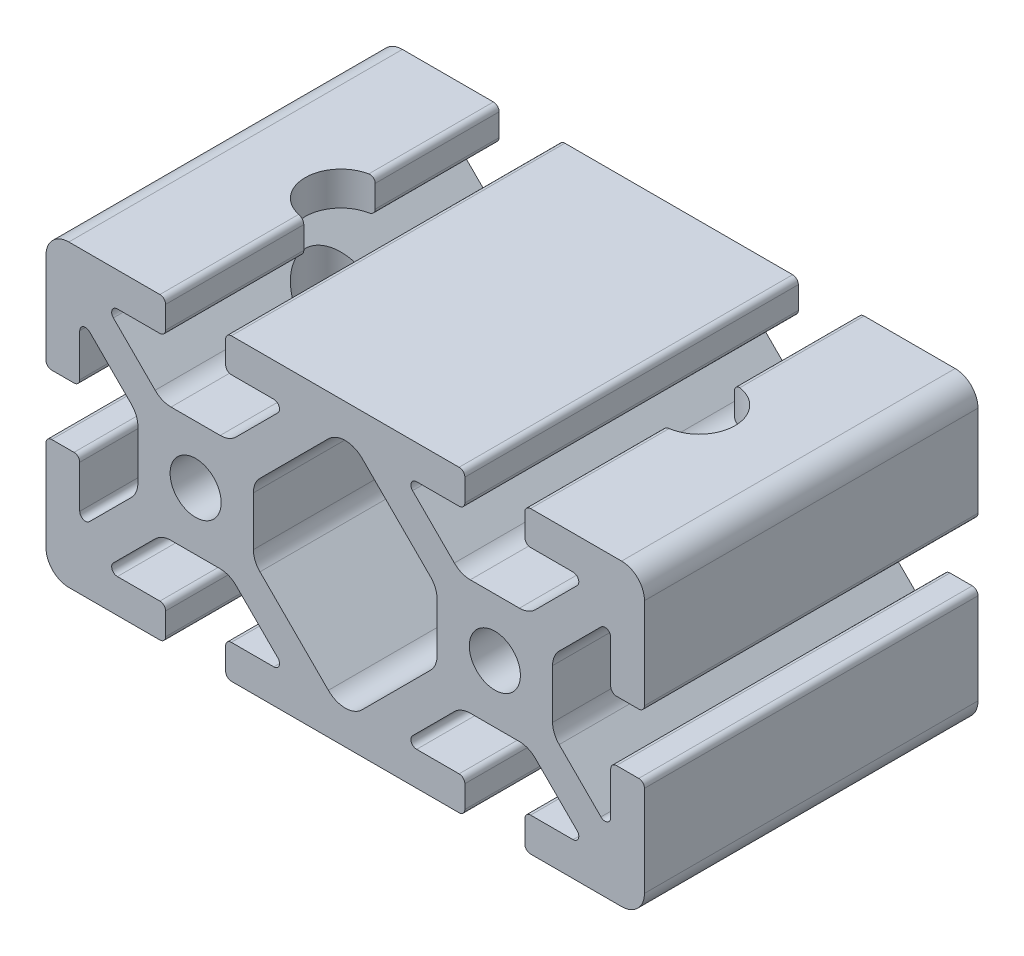
SolidWorks part; units mm, degrees
ref_plane "Front Plane" through (0, 0, 0) normal (0, 0, 1) x (1, 0, 0)
ref_plane "Top Plane" through (0, 0, 0) normal (0, 1, 0) x (1, 0, 0)
ref_plane "Right Plane" through (0, 0, 0) normal (1, 0, 0) x (0, 0, -1)
sketch "Sketch1" plane through (0, 0, 0) normal (0, 0, 1) x (1, 0, 0)
  line L0 (0, 19.939) -> (0, -19.939) construction
  line L1 (-19.939, 0) -> (19.939, 0) construction
  line L2 (-19.939, 16.891) -> (-19.939, 4.7625)
  line L3 (-16.891, 19.939) -> (-4.7625, 19.939)
  line L4 (-4.0005, 19.177) -> (-4.0005, 16.2052)
  line L5 (-4.7625, 15.4432) -> (-10.4246, 15.4432)
  line L6 (-10.9634, 14.1424) -> (-5.395, 8.5741)
  line L7 (-14.1424, 10.9634) -> (-8.5741, 5.395)
  line L8 (-15.4432, 10.4246) -> (-15.4432, 4.7625)
  line L9 (-16.2052, 4.0005) -> (-19.177, 4.0005)
  line L10 (0, 0) -> (-19.939, 19.939) construction
  line L11 (-3.2757, 7.6962) -> (3.2757, 7.6962)
  line L12 (-7.6962, 3.2757) -> (-7.6962, -3.2757)
  line L16 (35.1155, 19.939) -> (4.7625, 19.939)
  line L17 (4.0005, 19.177) -> (4.0005, 16.2052)
  line L18 (4.7625, 15.4432) -> (10.4246, 15.4432)
  line L19 (7.6962, 3.2757) -> (7.6962, -3.2757)
  line L20 (10.9634, 14.1424) -> (5.395, 8.5741)
  line L21 (17.6911, 14.5121) -> (8.5741, 5.395)
  line L22 (-16.2052, -4.0005) -> (-19.177, -4.0005)
  line L23 (-15.4432, -10.4246) -> (-15.4432, -4.7625)
  line L24 (-14.1424, -10.9634) -> (-8.5741, -5.395)
  line L25 (-10.9634, -14.1424) -> (-5.395, -8.5741)
  line L26 (-4.7625, -15.4432) -> (-10.4246, -15.4432)
  line L27 (-4.0005, -19.177) -> (-4.0005, -16.2052)
  line L28 (-16.891, -19.939) -> (-4.7625, -19.939)
  line L29 (-19.939, -16.891) -> (-19.939, -4.7625)
  line L31 (19.939, -19.939) -> (4.7625, -19.939)
  line L32 (4.0005, -19.177) -> (4.0005, -16.2052)
  line L33 (4.7625, -15.4432) -> (10.4246, -15.4432)
  line L34 (10.9634, -14.1424) -> (5.395, -8.5741)
  line L35 (17.6911, -14.5121) -> (8.5741, -5.395)
  line L38 (-3.2757, -7.6962) -> (3.2757, -7.6962)
  line L39 (19.939, 0) -> (19.939, -19.939) construction
  line L40 (43.1537, -7.6962) -> (36.6023, -7.6962)
  line L43 (22.1869, -14.5121) -> (31.3039, -5.395)
  line L44 (28.9146, -14.1424) -> (34.483, -8.5741)
  line L45 (35.1155, -15.4432) -> (29.4534, -15.4432)
  line L46 (35.8775, -19.177) -> (35.8775, -16.2052)
  line L47 (19.939, -19.939) -> (35.1155, -19.939)
  line L48 (59.817, -16.891) -> (59.817, -4.7625)
  line L49 (56.769, -19.939) -> (44.6405, -19.939)
  line L50 (43.8785, -19.177) -> (43.8785, -16.2052)
  line L51 (44.6405, -15.4432) -> (50.3026, -15.4432)
  line L52 (50.8414, -14.1424) -> (45.273, -8.5741)
  line L53 (54.0204, -10.9634) -> (48.4521, -5.395)
  line L54 (55.3212, -10.4246) -> (55.3212, -4.7625)
  line L55 (56.0832, -4.0005) -> (59.055, -4.0005)
  line L56 (22.1869, 14.5121) -> (31.3039, 5.395)
  line L57 (28.9146, 14.1424) -> (34.483, 8.5741)
  line L58 (32.1818, 3.2757) -> (32.1818, -3.2757)
  line L59 (35.1155, 15.4432) -> (29.4534, 15.4432)
  line L60 (35.8775, 19.177) -> (35.8775, 16.2052)
  line L64 (47.5742, 3.2757) -> (47.5742, -3.2757)
  line L65 (43.1537, 7.6962) -> (36.6023, 7.6962)
  line L66 (56.0832, 4.0005) -> (59.055, 4.0005)
  line L67 (55.3212, 10.4246) -> (55.3212, 4.7625)
  line L68 (54.0204, 10.9634) -> (48.4521, 5.395)
  line L69 (50.8414, 14.1424) -> (45.273, 8.5741)
  line L70 (44.6405, 15.4432) -> (50.3026, 15.4432)
  line L71 (43.8785, 19.177) -> (43.8785, 16.2052)
  line L72 (56.769, 19.939) -> (44.6405, 19.939)
  line L73 (59.817, 16.891) -> (59.817, 4.7625)
  circle A0 centre (0, 0) radius 3.4036
  arc A1 (-19.939, 16.891) -> (-16.891, 19.939) centre (-16.891, 16.891) cw
  arc A2 (-14.1424, 10.9634) -> (-15.4432, 10.4246) centre (-14.6812, 10.4246) ccw
  arc A3 (-10.4246, 15.4432) -> (-10.9634, 14.1424) centre (-10.4246, 14.6812) ccw
  arc A4 (-4.7625, 19.939) -> (-4.0005, 19.177) centre (-4.7625, 19.177) cw
  arc A5 (-19.939, 4.7625) -> (-19.177, 4.0005) centre (-19.177, 4.7625) ccw
  arc A6 (-15.4432, 4.7625) -> (-16.2052, 4.0005) centre (-16.2052, 4.7625) cw
  arc A7 (-4.0005, 16.2052) -> (-4.7625, 15.4432) centre (-4.7625, 16.2052) cw
  arc A8 (-3.2757, 7.6962) -> (-5.395, 8.5741) centre (-3.2757, 10.6934) cw
  arc A9 (-7.6962, 3.2757) -> (-8.5741, 5.395) centre (-10.6934, 3.2757) ccw
  arc A10 (22.1869, 14.5121) -> (17.6911, 14.5121) centre (19.939, 12.2642) ccw
  arc A11 (17.6911, -14.5121) -> (22.1869, -14.5121) centre (19.939, -12.2642) ccw
  arc A13 (4.7625, 19.939) -> (4.0005, 19.177) centre (4.7625, 19.177) ccw
  arc A14 (4.0005, 16.2052) -> (4.7625, 15.4432) centre (4.7625, 16.2052) ccw
  arc A15 (3.2757, 7.6962) -> (5.395, 8.5741) centre (3.2757, 10.6934) ccw
  arc A16 (7.6962, 3.2757) -> (8.5741, 5.395) centre (10.6934, 3.2757) cw
  arc A18 (10.4246, 15.4432) -> (10.9634, 14.1424) centre (10.4246, 14.6812) cw
  arc A19 (-7.6962, -3.2757) -> (-8.5741, -5.395) centre (-10.6934, -3.2757) cw
  arc A20 (-3.2757, -7.6962) -> (-5.395, -8.5741) centre (-3.2757, -10.6934) ccw
  arc A21 (-4.0005, -16.2052) -> (-4.7625, -15.4432) centre (-4.7625, -16.2052) ccw
  arc A22 (-15.4432, -4.7625) -> (-16.2052, -4.0005) centre (-16.2052, -4.7625) ccw
  arc A23 (-19.939, -4.7625) -> (-19.177, -4.0005) centre (-19.177, -4.7625) cw
  arc A24 (-4.7625, -19.939) -> (-4.0005, -19.177) centre (-4.7625, -19.177) ccw
  arc A25 (-10.4246, -15.4432) -> (-10.9634, -14.1424) centre (-10.4246, -14.6812) cw
  arc A26 (-14.1424, -10.9634) -> (-15.4432, -10.4246) centre (-14.6812, -10.4246) cw
  arc A27 (-19.939, -16.891) -> (-16.891, -19.939) centre (-16.891, -16.891) ccw
  arc A30 (10.4246, -15.4432) -> (10.9634, -14.1424) centre (10.4246, -14.6812) ccw
  arc A31 (4.7625, -19.939) -> (4.0005, -19.177) centre (4.7625, -19.177) cw
  arc A34 (4.0005, -16.2052) -> (4.7625, -15.4432) centre (4.7625, -16.2052) cw
  arc A35 (3.2757, -7.6962) -> (5.395, -8.5741) centre (3.2757, -10.6934) cw
  arc A36 (7.6962, -3.2757) -> (8.5741, -5.395) centre (10.6934, -3.2757) ccw
  arc A37 (32.1818, -3.2757) -> (31.3039, -5.395) centre (29.1846, -3.2757) cw
  arc A38 (36.6023, -7.6962) -> (34.483, -8.5741) centre (36.6023, -10.6934) ccw
  arc A39 (35.8775, -16.2052) -> (35.1155, -15.4432) centre (35.1155, -16.2052) ccw
  arc A41 (35.1155, -19.939) -> (35.8775, -19.177) centre (35.1155, -19.177) ccw
  arc A42 (29.4534, -15.4432) -> (28.9146, -14.1424) centre (29.4534, -14.6812) cw
  arc A44 (59.817, -16.891) -> (56.769, -19.939) centre (56.769, -16.891) cw
  arc A45 (54.0204, -10.9634) -> (55.3212, -10.4246) centre (54.5592, -10.4246) ccw
  arc A46 (50.3026, -15.4432) -> (50.8414, -14.1424) centre (50.3026, -14.6812) ccw
  arc A47 (44.6405, -19.939) -> (43.8785, -19.177) centre (44.6405, -19.177) cw
  arc A48 (59.817, -4.7625) -> (59.055, -4.0005) centre (59.055, -4.7625) ccw
  arc A49 (55.3212, -4.7625) -> (56.0832, -4.0005) centre (56.0832, -4.7625) cw
  arc A50 (43.8785, -16.2052) -> (44.6405, -15.4432) centre (44.6405, -16.2052) cw
  arc A51 (43.1537, -7.6962) -> (45.273, -8.5741) centre (43.1537, -10.6934) cw
  arc A52 (47.5742, -3.2757) -> (48.4521, -5.395) centre (50.5714, -3.2757) ccw
  arc A53 (29.4534, 15.4432) -> (28.9146, 14.1424) centre (29.4534, 14.6812) ccw
  arc A55 (32.1818, 3.2757) -> (31.3039, 5.395) centre (29.1846, 3.2757) ccw
  arc A56 (36.6023, 7.6962) -> (34.483, 8.5741) centre (36.6023, 10.6934) cw
  arc A57 (35.8775, 16.2052) -> (35.1155, 15.4432) centre (35.1155, 16.2052) cw
  arc A58 (35.1155, 19.939) -> (35.8775, 19.177) centre (35.1155, 19.177) cw
  arc A60 (47.5742, 3.2757) -> (48.4521, 5.395) centre (50.5714, 3.2757) cw
  arc A61 (43.1537, 7.6962) -> (45.273, 8.5741) centre (43.1537, 10.6934) ccw
  arc A62 (43.8785, 16.2052) -> (44.6405, 15.4432) centre (44.6405, 16.2052) ccw
  arc A63 (55.3212, 4.7625) -> (56.0832, 4.0005) centre (56.0832, 4.7625) ccw
  arc A64 (59.817, 4.7625) -> (59.055, 4.0005) centre (59.055, 4.7625) cw
  arc A65 (44.6405, 19.939) -> (43.8785, 19.177) centre (44.6405, 19.177) ccw
  arc A66 (50.3026, 15.4432) -> (50.8414, 14.1424) centre (50.3026, 14.6812) cw
  arc A67 (54.0204, 10.9634) -> (55.3212, 10.4246) centre (54.5592, 10.4246) cw
  arc A68 (59.817, 16.891) -> (56.769, 19.939) centre (56.769, 16.891) ccw
  circle A69 centre (39.878, 0) radius 3.4036
  point P29 (-19.939, 4.0005)
  point P32 (-15.4432, 4.0005)
  point P36 (-4.5172, 7.6962)
  point P68 (0, 7.6962)
  point P219 (39.878, 7.6962)
  dimension "D4" = 6.8072
  dimension "D5" = 3.048
  dimension "D6" = 0.762
  dimension "D9" = 0.762
  dimension "D10" = 0.762
  dimension "D11" = 4.4958
  dimension "D13" = 2.9972
  dimension "D1" = 39.878
  dimension "D2" = 39.878
  dimension "D3" = 12.2428
  dimension "D7" = 8.001
  dimension "D8" = 4.4958
extrude "Extrude1" add sketch "Sketch1" along normal mid plane 44.45
sketch "Sketch2" plane through (0, 19.939, 0) normal (0, 1, 0) x (-1, 0, 0)
  line L0 (4.7625, -22.225) -> (16.891, -22.225) construction
  line L3 (19.939, 22.225) -> (19.939, -22.225) construction
  line L4 (-56.769, -22.225) -> (-44.6405, -22.225) construction
  circle A0 centre (-43.937, -0.95) radius 4.7625
  circle A1 centre (3.815, -0.95) radius 4.7625
  dimension "D1" = 9.525
  dimension "D2" = 47.752
  dimension "D3" = 21.275
  dimension "D4" = 9.525
  dimension "D5" = 21.275
  dimension "D6" = 16.124
extrude "Cut-Extrude1" cut sketch "Sketch2" against normal up to surface (39.878 mm away) up to face at (19.939, -19.939, 0)
equation "\"D2@Sketch1\" = \"D1@Sketch1\""
